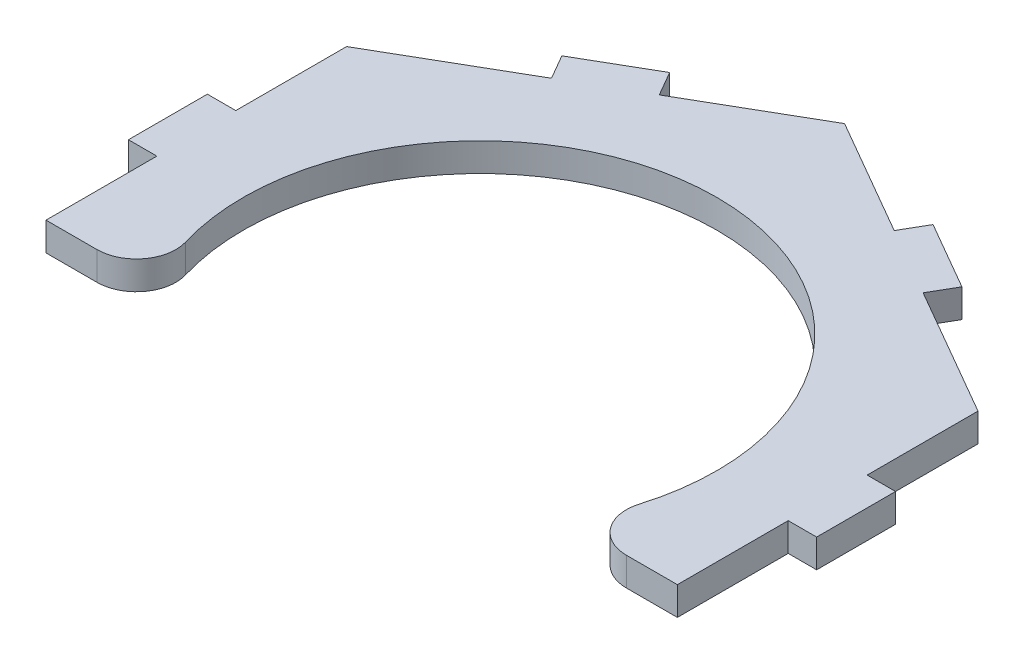
SolidWorks part; units mm, degrees
ref_plane "Front Plane" through (0, 0, 0) normal (0, 0, 1) x (1, 0, 0)
ref_plane "Top Plane" through (0, 0, 0) normal (0, 1, 0) x (1, 0, 0)
ref_plane "Right Plane" through (0, 0, 0) normal (1, 0, 0) x (0, 0, -1)
sketch "Sketch1" plane through (0, 0, 0) normal (0, 1, 0) x (1, 0, 0)
  line L0 (-50.8, -19.05) -> (-42.5971, -19.05)
  line L1 (50.8, -19.05) -> (50.8, 29.3294)
  line L2 (50.8, 29.3294) -> (0, 58.6588)
  line L3 (0, 58.6588) -> (-50.8, 29.3294)
  line L4 (-50.8, 29.3294) -> (-50.8, -19.05)
  line L7 (-25.4, -43.9941) -> (-9.8224, -52.9878) [skipped]
  line L8 (25.4, -43.9941) -> (40.9776, -35.0003) [skipped]
  line L9 (50.8, -19.05) -> (42.5971, -19.05)
  arc A0 (50.8, 0) -> (-50.8, 0) centre (0, 0) ccw construction
  arc A1 (36.5118, -10.8857) -> (-36.5118, -10.8857) centre (0, 0) ccw
  arc A2 (42.5971, -19.05) -> (36.5118, -10.8857) centre (42.5971, -12.7) cw
  arc A3 (-42.5971, -19.05) -> (-36.5118, -10.8857) centre (-42.5971, -12.7) ccw
  point P8 (-36.1544, 20.8738)
  dimension "D1" = 38.1
  dimension "D2" = 50.8
  dimension "D4" = 6.35
  dimension "D3" = 19.05
extrude "Boss-Extrude1" add sketch "Sketch1" along normal blind 4.572
sketch "Sketch2" plane through (0, 4.572, 0) normal (0, 1, 0) x (1, 0, 0)
  line L0 (-50.8, 11.4897) -> (-55.372, 11.4897)
  line L1 (-50.8, 29.3294) -> (-50.8, -19.05) construction
  line L2 (-55.372, 11.4897) -> (-55.372, -1.2103)
  line L3 (-55.372, -1.2103) -> (-50.8, -1.2103)
  line L4 (-29.9028, 41.3944) -> (-32.1888, 45.3539)
  line L5 (0, 58.6588) -> (-50.8, 29.3294) construction
  line L6 (-32.1888, 45.3539) -> (-21.1903, 51.7039)
  line L7 (-21.1903, 51.7039) -> (-18.9043, 47.7444)
  line L8 (18.9043, 47.7444) -> (21.1903, 51.7039)
  line L9 (50.8, 29.3294) -> (0, 58.6588) construction
  line L10 (21.1903, 51.7039) -> (32.1888, 45.3539)
  line L11 (32.1888, 45.3539) -> (29.9028, 41.3944)
  line L13 (50.8, 11.4897) -> (55.372, 11.4897)
  line L14 (50.8, -19.05) -> (50.8, 29.3294) construction
  line L15 (55.372, 11.4897) -> (55.372, -1.2103)
  line L16 (55.372, -1.2103) -> (50.8, -1.2103)
  line L20 (-50.8, -1.2103) -> (-50.8, 11.4897)
  line L21 (-29.9028, 41.3944) -> (-18.9043, 47.7444)
  line L22 (18.9043, 47.7444) -> (29.9028, 41.3944)
  line L23 (50.8, 11.4897) -> (50.8, -1.2103)
  point P24 (-50.8, 5.1397)
  point P25 (-55.372, 5.1397)
  point P26 (55.372, 5.1397)
  dimension "D1" = 24.13
  dimension "D2" = 24.13
  dimension "D3" = 12.7
  dimension "D4" = 4.572
extrude "Boss-Extrude2" add sketch "Sketch2" against normal blind 4.572
